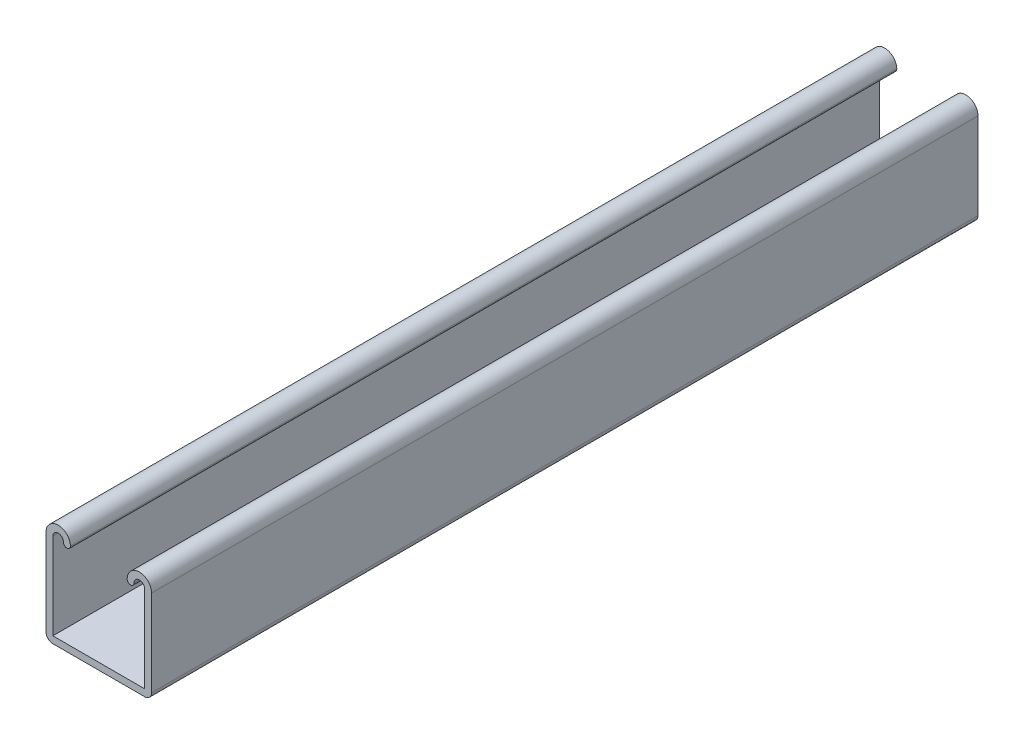
SolidWorks part; units mm, degrees
material "普通碳钢"
ref_plane "前视基准面" through (0, 0, 0) normal (0, 0, 1) x (1, 0, 0)
ref_plane "上视基准面" through (0, 0, 0) normal (0, 1, 0) x (1, 0, 0)
ref_plane "右视基准面" through (0, 0, 0) normal (1, 0, 0) x (0, 0, -1)
sketch "草图1" plane through (0, 0, 0) normal (0, 0, 1) x (1, 0, 0)
  line L0 (0, 0) -> (35.98, 0)
  line L1 (17.99, 2.6924) -> (17.99, -3.3917) construction
  line L2 (35.98, 2.6924) -> (0, 2.6924)
  line L3 (35.98, 19.6088) -> (0, 19.6088) construction
  line L4 (35.98, 2.6924) -> (35.98, 36.5252)
  line L5 (38.6724, 2.6924) -> (38.6724, 36.5252)
  line L6 (-2.6924, 2.6924) -> (-2.6924, 36.5252)
  line L7 (0, 2.6924) -> (0, 36.5252)
  line L8 (17.99, 19.6088) -> (17.99, 2.6924) construction
  arc A0 (35.98, 0) -> (38.6724, 2.6924) centre (35.98, 2.6924) ccw
  arc A1 (35.98, 36.5252) -> (31.8144, 36.5252) centre (33.8972, 36.5252) ccw
  arc A2 (38.6724, 36.5252) -> (29.122, 36.5252) centre (33.8972, 36.5252) ccw
  arc A3 (29.122, 36.5252) -> (31.8144, 36.5252) centre (30.4682, 36.5252) ccw
  arc A4 (6.858, 36.5252) -> (4.1656, 36.5252) centre (5.5118, 36.5252) cw
  arc A5 (-2.6924, 36.5252) -> (6.858, 36.5252) centre (2.0828, 36.5252) cw
  arc A6 (0, 36.5252) -> (4.1656, 36.5252) centre (2.0828, 36.5252) cw
  arc A7 (0, 0) -> (-2.6924, 2.6924) centre (0, 2.6924) cw
  point P25 (17.99, 19.6088)
extrude "凸台-拉伸1" add sketch "草图1" along normal blind 323.85
ref_plane "基准面1" through (0, 0, 0) normal (0, -1, 0) x (-1, 0, 0)
sketch "草图2" plane through (0, 0, 0) normal (0, -1, 0) x (-1, 0, 0)
  line L0 (-17.99, 0) -> (-17.99, -28.448) construction
  line L1 (0, 0) -> (-35.98, 0) construction
  line L2 (-17.99, -28.448) -> (-17.99, -76.2) construction
  line L3 (-35.98, -161.925) -> (0, -161.925) construction
  line L4 (-35.98, -323.85) -> (-35.98, 0) construction
  line L5 (0, -323.85) -> (0, 0) construction
  circle A0 centre (-17.99, -28.448) radius 7.112
  circle A1 centre (-17.99, -76.2) radius 7.112
  circle A2 centre (-17.99, -295.402) radius 7.112
  circle A3 centre (-17.99, -247.65) radius 7.112
  dimension "D1" = 28.448
  dimension "D2" = 47.752
extrude "切除-拉伸1" cut sketch "草图2" against normal through all
